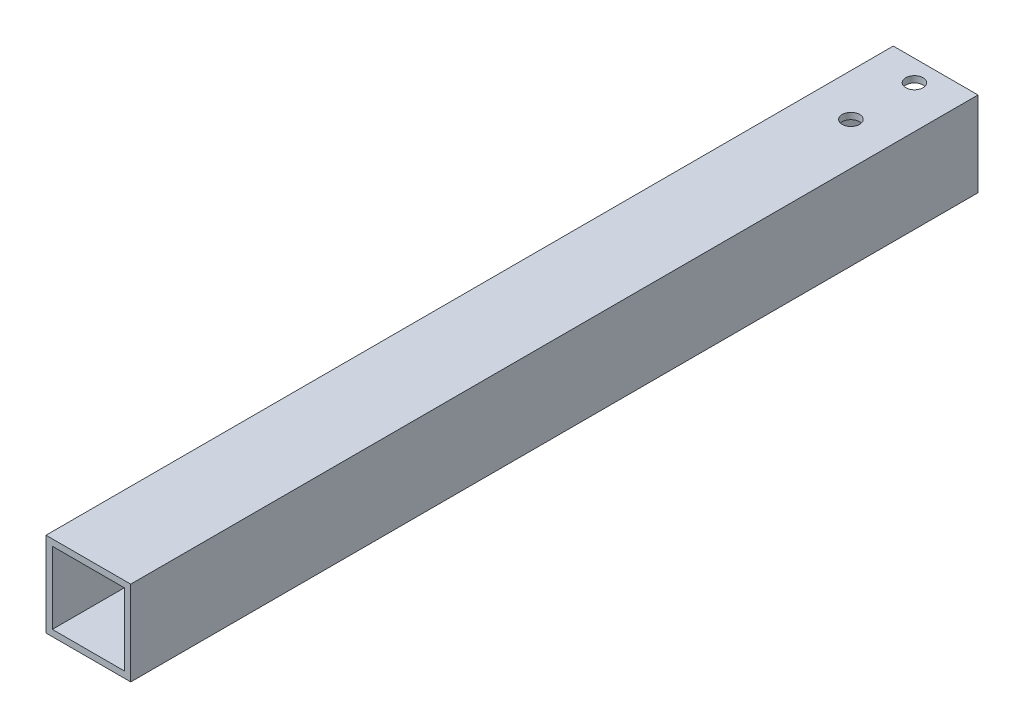
SolidWorks part; units mm, degrees
ref_plane "前视基准面" through (0, 0, 0) normal (0, 0, 1) x (1, 0, 0)
ref_plane "上视基准面" through (0, 0, 0) normal (0, 1, 0) x (1, 0, 0)
ref_plane "右视基准面" through (0, 0, 0) normal (1, 0, 0) x (0, 0, -1)
sketch "草图1" plane through (0, 0, 0) normal (0, 0, 1) x (1, 0, 0)
  line L1 (-10, 10) -> (10, 10)
  line L2 (-10, 10) -> (-10, -10)
  line L3 (-10, -10) -> (10, -10)
  line L4 (10, 10) -> (10, -10)
  line L5 (-10, 10) -> (10, -10) construction
  line L6 (-10, -10) -> (10, 10) construction
  line L7 (-8.5, 8.5) -> (8.5, 8.5)
  line L8 (-8.5, 8.5) -> (-8.5, -8.5)
  line L9 (-8.5, -8.5) -> (8.5, -8.5)
  line L10 (8.5, 8.5) -> (8.5, -8.5)
  line L11 (-8.5, 8.5) -> (8.5, -8.5) construction
  line L12 (-8.5, -8.5) -> (8.5, 8.5) construction
  point P0 (0, 0)
  point P5 (0, 0)
  dimension "D1" = 20
  dimension "D2" = 20
  dimension "D3" = 1.5
  dimension "D4" = 1.5
extrude "凸台-拉伸1" add sketch "草图1" along normal blind 200
sketch "草图3" plane through (0, 10, 0) normal (0, 1, 0) x (1, 0, 0)
  circle A0 centre (0, -5) radius 2.05
  circle A1 centre (0, -20) radius 2.05
  dimension "D1" = 4.1
  dimension "D2" = 5
  dimension "D3" = 15
extrude "切除-拉伸1" cut sketch "草图3" against normal blind 24
